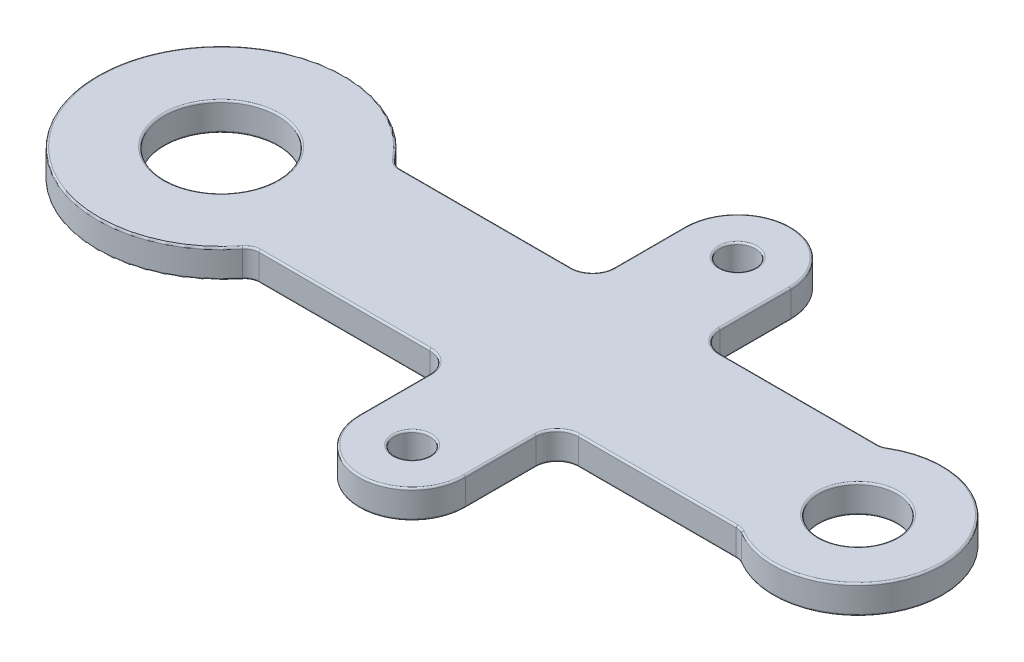
SolidWorks part; units mm, degrees
ref_plane "前视基准面" through (0, 0, 0) normal (0, 0, 1) x (1, 0, 0)
ref_plane "上视基准面" through (0, 0, 0) normal (0, 1, 0) x (1, 0, 0)
ref_plane "右视基准面" through (0, 0, 0) normal (1, 0, 0) x (0, 0, -1)
sketch "草图1" plane through (0, 0, 0) normal (0, 1, 0) x (1, 0, 0)
  line L0 (-79.8254, 0) -> (43.5663, 0) construction
  line L1 (0, 81.5805) -> (0, -29.6577) construction
  line L2 (28.7194, 20.0049) -> (85, 20.0049)
  line L3 (28.7194, -20.0049) -> (85, -20.0049)
  line L4 (115, 20.0049) -> (166.7409, 20.0049)
  line L5 (115, -20.0049) -> (166.7409, -20.0049)
  line L7 (85, 46) -> (85, 20.0049)
  line L8 (115, 46) -> (115, 20.0049)
  line L9 (115, -46) -> (115, -20.0049)
  line L10 (85, -46) -> (85, -20.0049)
  circle A0 centre (0, 0) radius 16
  arc A1 (28.7194, 20.0049) -> (28.7194, -20.0049) centre (0, 0) ccw
  circle A2 centre (100, 46) radius 5
  circle A3 centre (180, 0) radius 11
  arc A4 (166.7409, -20.0049) -> (166.7409, 20.0049) centre (180, 0) ccw
  circle A5 centre (100, -46) radius 5
  arc A8 (115, 46) -> (85, 46) centre (100, 46) ccw
  arc A9 (115, -46) -> (85, -46) centre (100, -46) cw
  point P9 (180, 0)
  point P13 (28.7194, 20.0049)
  point P24 (100, 0)
  point P29 (85, 46)
  point P30 (115, 46)
extrude "凸台-拉伸2" add sketch "草图1" along normal blind 8
fillet "圆角1" radius 6 1 edges at (85, 4, -20.0049)
fillet "圆角2" radius 6 1 edges at (115, 4, -20.0049)
fillet "圆角3" radius 6 1 edges at (85, 4, 20.0049)
fillet "圆角4" radius 6 1 edges at (115, 4, 20.0049)
fillet "圆角5" radius 4 1 edges at (166.7409, 4, 20.0049)
fillet "圆角6" radius 4 1 edges at (28.7194, 4, 20.0049)
fillet "圆角7" radius 4 1 edges at (166.7409, 4, -20.0049)
fillet "圆角8" radius 4 1 edges at (28.7194, 4, -20.0049)
fillet "圆角9" radius 0.5 48 edges at (180, 8, 11) (100, 8, -41) (0, 8, 16) (100, 8, 41) (54.8685, 8, -20.0049) (83.2426, 8, -21.7622) (85, 8, -36.0024) (100, 8, -61) (115, 8, -36.0024) (116.7574, 8, -21.7622) (143.293, 8, -20.0049) (166.6543, 8, -20.1502) (204, 8, 0) (166.6543, 8, 20.1502) (143.293, 8, 20.0049) (116.7574, 8, 21.7622) (115, 8, 36.0024) (100, 8, 61) (85, 8, 36.0024) (83.2426, 8, 21.7622) (54.8685, 8, 20.0049) (28.9832, 8, 20.4099) (-35, 8, 0) (28.9832, 8, -20.4099) (180, 0, 11) (100, 0, 41) (100, 0, -41) (0, 0, 16) (28.9832, 0, 20.4099) (54.8685, 0, 20.0049) (83.2426, 0, 21.7622) (85, 0, 36.0024) (100, 0, 61) (115, 0, 36.0024) (116.7574, 0, 21.7622) (143.293, 0, 20.0049) (166.6543, 0, 20.1502) (204, 0, 0) (166.6543, 0, -20.1502) (143.293, 0, -20.0049) (116.7574, 0, -21.7622) (115, 0, -36.0024) (100, 0, -61) (85, 0, -36.0024) (83.2426, 0, -21.7622) (54.8685, 0, -20.0049) (28.9832, 0, -20.4099) (-35, 0, 0)
